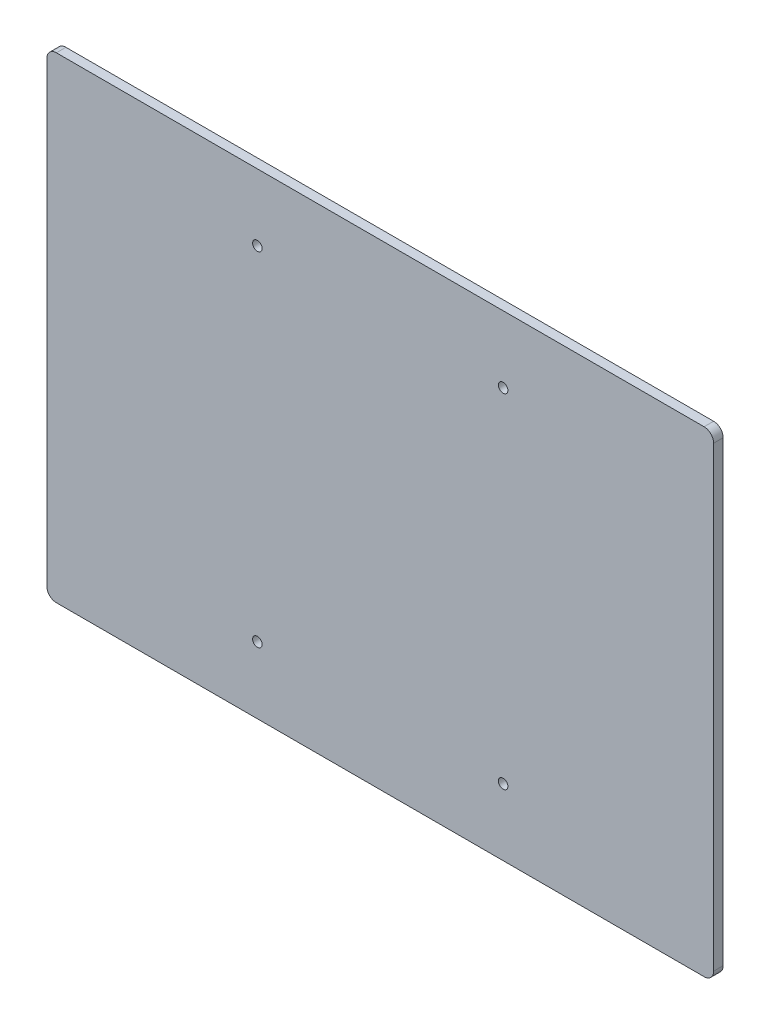
SolidWorks part; units mm, degrees
ref_plane "Plan de face" through (0, 0, 0) normal (0, 0, 1) x (1, 0, 0)
ref_plane "Plan de dessus" through (0, 0, 0) normal (0, 1, 0) x (1, 0, 0)
ref_plane "Plan de droite" through (0, 0, 0) normal (1, 0, 0) x (0, 0, -1)
sketch "Esquisse1" plane through (0, 0, 0) normal (0, 0, 1) x (1, 0, 0)
  line L0 (-175, 250) -> (175, 0) construction
  line L1 (-175, 250) -> (175, 250)
  line L2 (-175, 250) -> (-175, 0)
  line L3 (-175, 0) -> (175, 0)
  line L4 (175, 250) -> (175, 0)
  line L5 (175, 250) -> (-175, 0) construction
  point P4 (0, 0)
  dimension "D1" = 250
  dimension "D2" = 350
extrude "Boss.-Extru.1" add sketch "Esquisse1" along normal blind 5
fillet "Congé1" radius 5 4 edges at (-175, 0, 2.5) (175, 0, 2.5) (175, 250, 2.5) (-175, 250, 2.5)
sketch "Esquisse2" plane through (0, 0, 0) normal (0, 0, 1) x (1, 0, 0)
  line L0 (175, 5) -> (175, 245) construction
  line L1 (-170, 0) -> (170, 0) construction
  line L2 (0, 0) -> (0, 250) construction
  line L3 (170, 250) -> (-170, 250) construction
  line L4 (175, 125) -> (-175, 125) construction
  line L5 (-175, 245) -> (-175, 5) construction
  circle A0 centre (64.5, 35) radius 2.5
  circle A1 centre (-64.5, 35) radius 2.5
  circle A2 centre (-64.5, 215) radius 2.5
  circle A3 centre (64.5, 215) radius 2.5
  dimension "D1" = 110.5
  dimension "D2" = 5
  dimension "D3" = 35
extrude "Enlèv. mat.-Extru.1" cut sketch "Esquisse2" along normal blind 10
